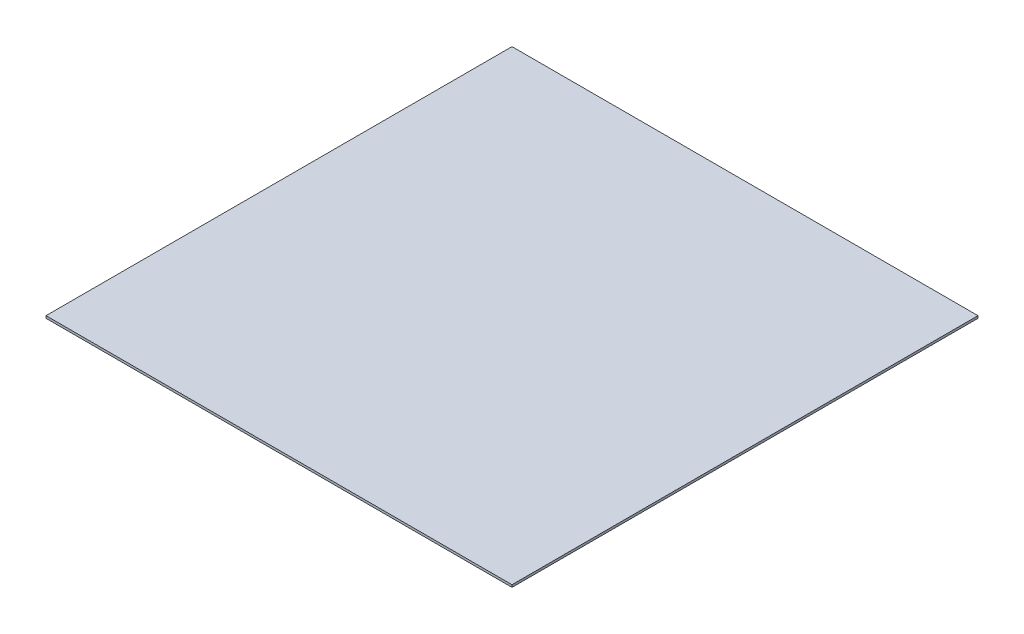
SolidWorks part; units mm, degrees
ref_plane "Plan de face" through (0, 0, 0) normal (0, 0, 1) x (1, 0, 0)
ref_plane "Plan de dessus" through (0, 0, 0) normal (0, 1, 0) x (1, 0, 0)
ref_plane "Plan de droite" through (0, 0, 0) normal (1, 0, 0) x (0, 0, -1)
sketch "Esquisse1" plane through (0, 0, 0) normal (0, 1, 0) x (1, 0, 0)
  line L1 (0, 0) -> (-2000, 0)
  line L2 (0, 0) -> (0, -2000)
  line L3 (0, -2000) -> (-2000, -2000)
  line L4 (-2000, 0) -> (-2000, -2000)
  dimension "D1" = 2000
extrude "Boss.-Extru.1" add sketch "Esquisse1" along normal blind 10
